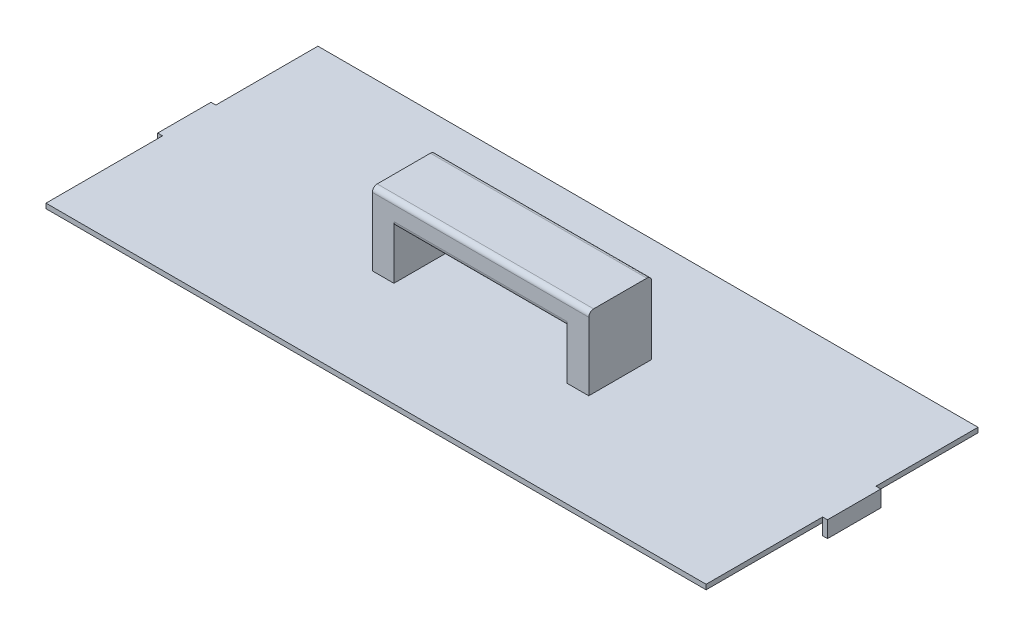
SolidWorks part; units mm, degrees
ref_plane "Front Plane" through (0, 0, 0) normal (0, 0, 1) x (1, 0, 0)
ref_plane "Top Plane" through (0, 0, 0) normal (0, 1, 0) x (1, 0, 0)
ref_plane "Right Plane" through (0, 0, 0) normal (1, 0, 0) x (0, 0, -1)
sketch "Sketch1" plane through (0, 0, 0) normal (0, 1, 0) x (1, 0, 0)
  line L5 (-56.3502, -64.7684) -> (74.5987, -64.7684) construction
  line L7 (76.9376, -62.782) -> (76.9376, -8.8109)
  line L8 (-56.3502, -64.7684) -> (74.5987, -64.7684)
  line L9 (-58.9112, -8.8109) -> (-58.9112, -62.7921)
  line L10 (-58.9112, -8.8109) -> (76.9376, -8.8109)
  line L11 (75.9344, -9.3109) -> (-57.9059, -9.3109) construction
  line L12 (-58.9112, -62.7921) -> (-58.9112, -64.7684)
  line L13 (-58.9112, -64.7684) -> (-56.3502, -64.7684)
  line L16 (74.5987, -64.7684) -> (76.9376, -64.7684)
  line L17 (76.9376, -64.7684) -> (76.9376, -62.782)
  dimension "D1" = 0.5
  dimension "D2" = 90
  dimension "D3" = 90
extrude "Boss-Extrude1" add sketch "Sketch1" along normal blind 1
sketch "Sketch3" plane through (0, 1, 0) normal (0, 1, 0) x (1, 0, 0)
  line L0 (-58.9112, -36.7896) -> (76.9376, -36.7896) construction
  line L1 (-58.9112, -8.8109) -> (-58.9112, -64.7684) construction
  line L2 (76.9376, -64.7684) -> (76.9376, -8.8109) construction
  line L3 (9.0132, -8.8109) -> (9.0132, -64.7684) construction
  line L4 (76.9376, -8.8109) -> (-58.9112, -8.8109) construction
  line L5 (-58.9112, -64.7684) -> (76.9376, -64.7684) construction
  line L6 (-13.2544, -43.2606) -> (-8.8215, -43.2606)
  line L7 (31.2808, -43.2606) -> (26.8479, -43.2606)
  line L8 (31.2808, -43.2606) -> (31.2808, -30.3187)
  line L9 (31.2808, -30.3187) -> (26.8479, -30.3187)
  line L10 (26.8479, -43.2606) -> (26.8479, -30.3187)
  line L11 (31.2808, -43.2606) -> (26.8479, -30.3187) construction
  line L12 (31.2808, -30.3187) -> (26.8479, -43.2606) construction
  line L13 (-8.8215, -43.2606) -> (-8.8215, -30.3187)
  line L14 (-13.2544, -30.3187) -> (-8.8215, -30.3187)
  line L15 (-13.2544, -43.2606) -> (-13.2544, -30.3187)
  point P12 (29.0644, -36.7896)
extrude "Boss-Extrude4" add sketch "Sketch3" along normal blind 10
sketch "Sketch4" plane through (0, 11, 0) normal (0, 1, 0) x (1, 0, 0)
  line L1 (-13.2544, -30.3187) -> (31.2808, -30.3187)
  line L2 (-13.2544, -30.3187) -> (-13.2544, -43.2606)
  line L3 (-13.2544, -43.2606) -> (31.2808, -43.2606)
  line L4 (31.2808, -30.3187) -> (31.2808, -43.2606)
extrude "Boss-Extrude6" add sketch "Sketch4" along normal blind 5 contours L2 L3 L4 L1
fillet "Fillet3" radius 1 2 edges at (9.0132, 16, 30.3187) (9.0132, 16, 43.2606)
fillet "Fillet4" radius 1 2 edges at (9.0132, 11, 30.3187) (9.0132, 11, 43.2606)
sketch "Sketch7" plane through (-58.9112, 0, 0) normal (-1, 0, 0) x (0, 0, 1)
  line L0 (8.8109, 1) -> (64.7684, 1) construction
  line L1 (29.8163, 1) -> (40.785, 1)
  line L2 (29.8163, 1) -> (29.8163, -2.3704)
  line L3 (29.8163, -2.3704) -> (40.785, -2.3704)
  line L4 (40.785, 1) -> (40.785, -2.3704)
extrude "Boss-Extrude7" add sketch "Sketch7" along normal blind 1
sketch "Sketch9" plane through (76.9376, 0, 0) normal (1, 0, 0) x (0, 0, -1)
  line L4 (-29.8163, -2.3704) -> (-29.8163, 1)
  line L5 (-40.785, -2.3704) -> (-29.8163, -2.3704)
  line L6 (-40.785, 1) -> (-40.785, -2.3704)
  line L7 (-29.8163, 1) -> (-40.785, 1)
  line L8 (-29.8163, -2.3704) -> (-29.8163, 1)
  line L9 (-40.785, -2.3704) -> (-29.8163, -2.3704)
  line L10 (-40.785, 1) -> (-40.785, -2.3704)
  line L11 (-29.8163, 1) -> (-40.785, 1)
  dimension "D1" = 0
extrude "Boss-Extrude8" add sketch "Sketch9" along normal blind 1
